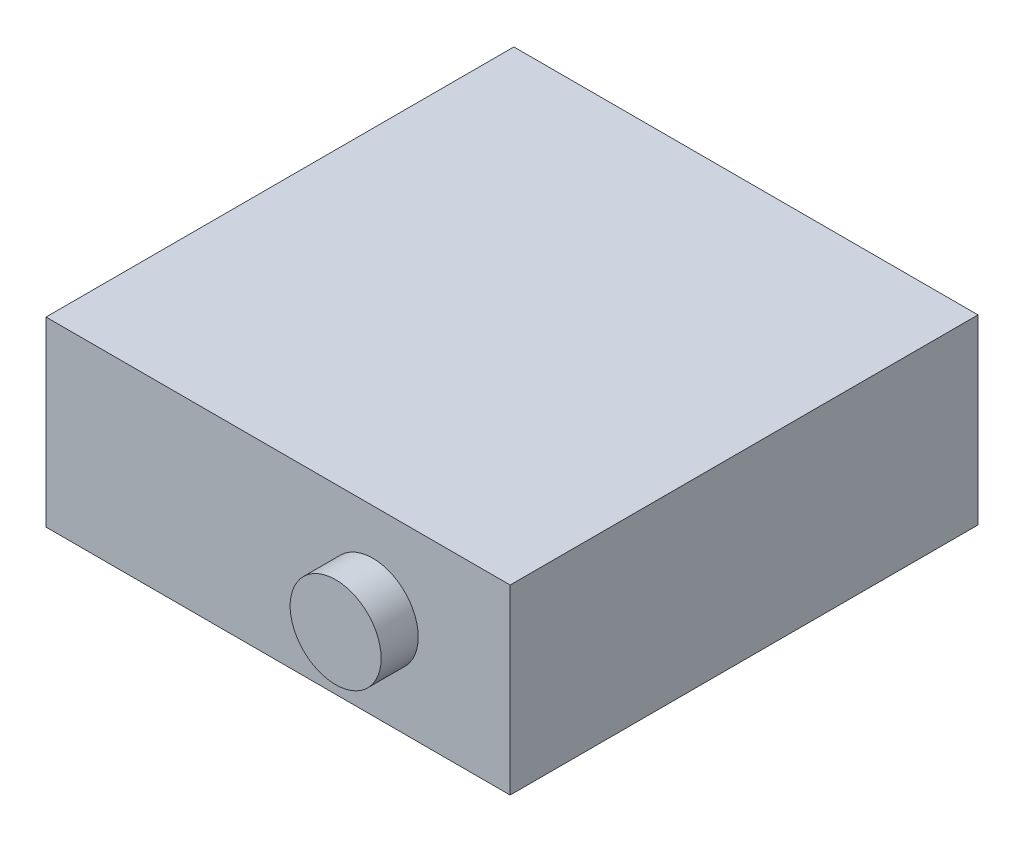
SolidWorks part; units mm, degrees
ref_plane "Front Plane" through (0, 0, 0) normal (0, 0, 1) x (1, 0, 0)
ref_plane "Top Plane" through (0, 0, 0) normal (0, 1, 0) x (1, 0, 0)
ref_plane "Right Plane" through (0, 0, 0) normal (1, 0, 0) x (0, 0, -1)
sketch "Sketch1" plane through (0, 0, 0) normal (0, 0, 1) x (1, 0, 0)
  line L1 (0, 0) -> (31.75, 0)
  line L2 (0, 0) -> (0, -12.446)
  line L3 (0, -12.446) -> (31.75, -12.446)
  line L4 (31.75, 0) -> (31.75, -12.446)
  dimension "D1" = 31.75
  dimension "D2" = 12.446
extrude "Boss-Extrude1" add sketch "Sketch1" along normal blind 32.004
sketch "Sketch2" plane through (0, 0, 32.004) normal (0, 0, 1) x (1, 0, 0)
  line L0 (0, 0) -> (0, -12.446) construction
  line L1 (0, -12.446) -> (31.75, -12.446) construction
  circle A0 centre (22.352, -6.223) radius 3.1115
  dimension "D1" = 6.223
  dimension "D2" = 22.352
  dimension "D3" = 6.223
extrude "Boss-Extrude2" add sketch "Sketch2" along normal blind 2.54 contours A0
